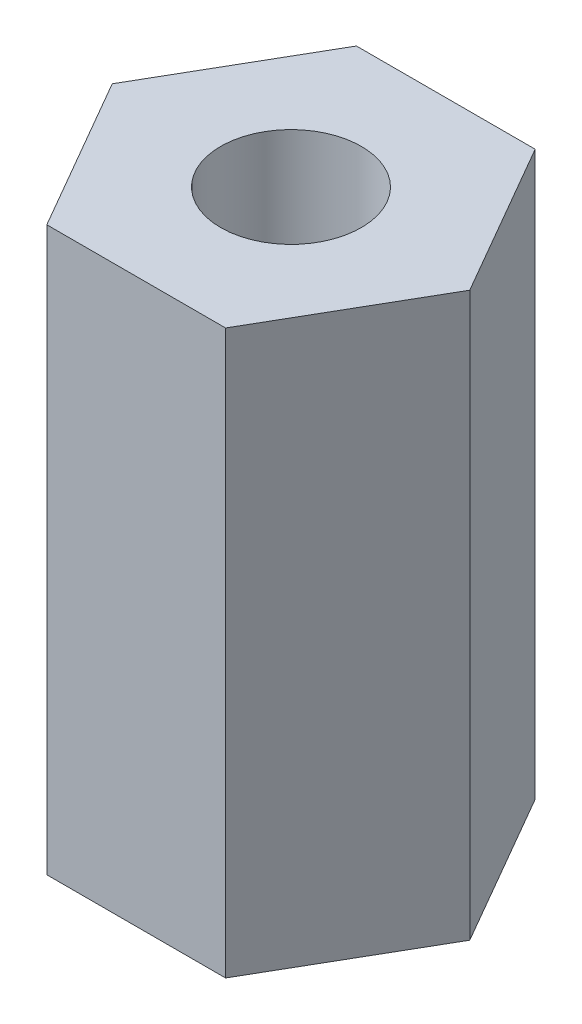
SolidWorks part; units mm, degrees
ref_plane "Front" through (0, 0, 0) normal (0, 0, 1) x (1, 0, 0)
ref_plane "Top" through (0, 0, 0) normal (0, 1, 0) x (1, 0, 0)
ref_plane "Right" through (0, 0, 0) normal (1, 0, 0) x (0, 0, -1)
sketch "Sketch1" plane through (0, 0, 0) normal (0, 1, 0) x (1, 0, 0)
  line L1 (3.1754, 0) -> (1.5877, 2.75)
  line L2 (1.5877, 2.75) -> (-1.5877, 2.75)
  line L3 (-1.5877, 2.75) -> (-3.1754, 0)
  line L4 (-3.1754, 0) -> (-1.5877, -2.75)
  line L5 (-1.5877, -2.75) -> (1.5877, -2.75)
  line L6 (1.5877, -2.75) -> (3.1754, 0)
  circle A0 centre (0, 0) radius 1.25
  circle A1 centre (0, 0) radius 2.75 construction
extrude "Boss-Extrude1" add sketch "Sketch1" along normal blind 10
